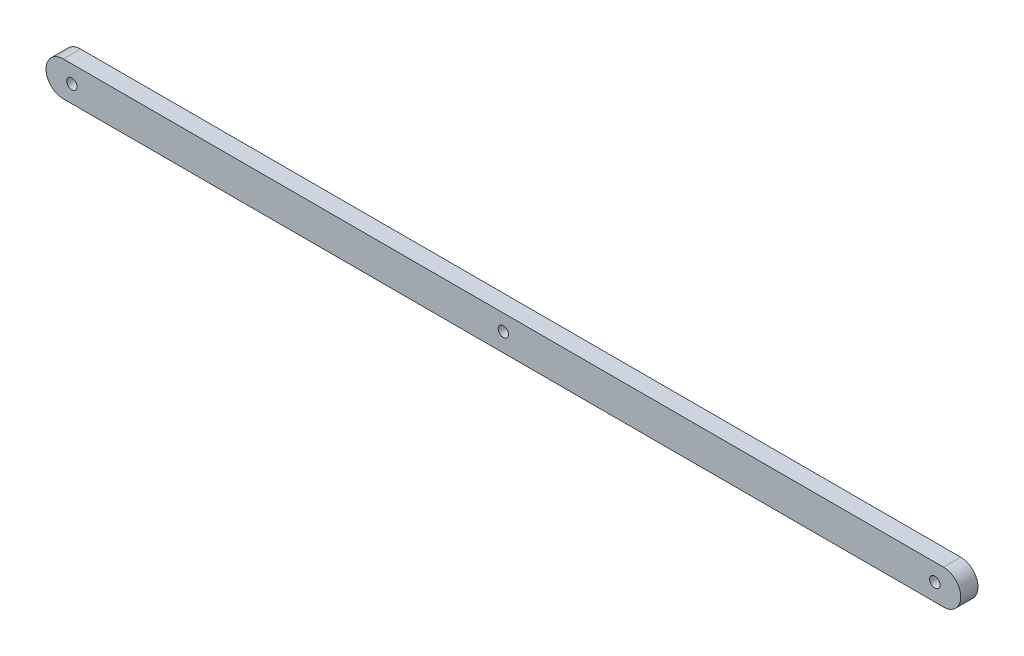
SolidWorks part; units mm, degrees
ref_plane "Plan de face" through (0, 0, 0) normal (0, 0, 1) x (1, 0, 0)
ref_plane "Plan de dessus" through (0, 0, 0) normal (0, 1, 0) x (1, 0, 0)
ref_plane "Plan de droite" through (0, 0, 0) normal (1, 0, 0) x (0, 0, -1)
sketch "Esquisse1" plane through (0, 0, 0) normal (0, 0, 1) x (1, 0, 0)
  line L1 (-122.6281, -8.2258) -> (387.3719, -8.2258)
  line L3 (-122.6281, -28.2258) -> (387.3719, -28.2258)
  circle A0 centre (-117.6281, -18.2258) radius 3
  circle A1 centre (382.3719, -18.2258) radius 3
  arc A2 (-122.6281, -28.2258) -> (-122.6281, -8.2258) centre (-122.6281, -18.2258) cw
  arc A3 (387.3719, -28.2258) -> (387.3719, -8.2258) centre (387.3719, -18.2258) ccw
  dimension "D2" = 6
  dimension "D3" = 6
  dimension "D5" = 10
  dimension "D1" = 500
  dimension "D4" = 20
  dimension "D6" = 5
  dimension "D7" = 5
extrude "Boss.-Extru.1" add sketch "Esquisse1" along normal blind 10
sketch "Esquisse2" plane through (0, 0, 10) normal (0, 0, 1) x (1, 0, 0)
  circle A0 centre (132.3709, -17.5102) radius 3
  circle A1 centre (-117.6281, -18.2258) radius 3 construction
  circle A2 centre (-117.6281, -18.2258) radius 3
  dimension "D1" = 6
  dimension "D2" = 250
extrude "Enlèv. mat.-Extru.1" cut sketch "Esquisse2" against normal blind 10
